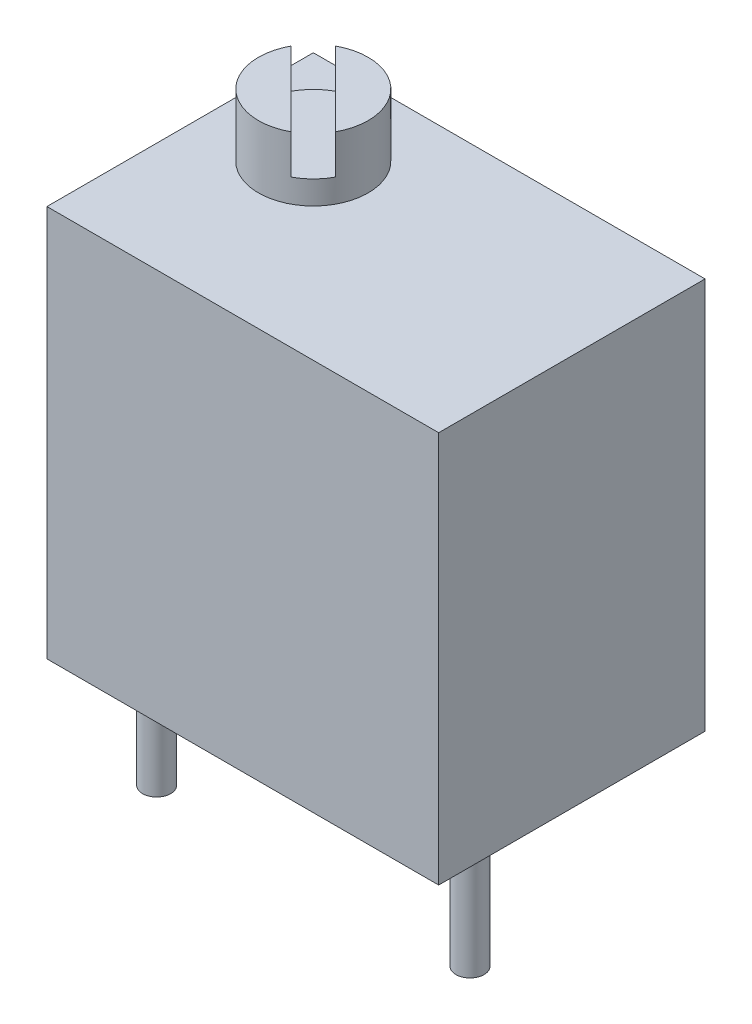
SolidWorks part; units mm, degrees
ref_plane "Front Plane" through (0, 0, 0) normal (0, 0, 1) x (1, 0, 0)
ref_plane "Top Plane" through (0, 0, 0) normal (0, 1, 0) x (1, 0, 0)
ref_plane "Right Plane" through (0, 0, 0) normal (1, 0, 0) x (0, 0, -1)
sketch "Sketch1" plane through (0, 0, 0) normal (0, 1, 0) x (1, 0, 0)
  line L1 (-0.762, -1.016) -> (5.588, -1.016)
  line L2 (-0.762, -1.016) -> (-0.762, 3.302)
  line L3 (-0.762, 3.302) -> (5.588, 3.302)
  line L4 (5.588, -1.016) -> (5.588, 3.302)
  dimension "D1" = 6.35
  dimension "D2" = 4.318
  dimension "D3" = 0.762
  dimension "D4" = 1.016
extrude "Extrude1" add sketch "Sketch1" along normal blind 6.35
sketch "Sketch2" plane through (0, 6.35, 0) normal (0, 1, 0) x (1, 0, 0)
  line L0 (-0.762, 3.302) -> (-0.762, -1.016) construction
  line L1 (5.588, 3.302) -> (-0.762, 3.302) construction
  circle A0 centre (0.762, 1.778) radius 0.889
  dimension "D3" = 1.778
  dimension "D1" = 1.524
  dimension "D2" = 1.524
extrude "Extrude2" add sketch "Sketch2" along normal blind 1.016
sketch "Sketch3" plane through (0, 7.366, 0) normal (0, 1, 0) x (1, 0, 0)
  line L0 (-0.1453, 2.3261) -> (1.3101, 0.8707)
  line L1 (-0.1453, 2.3261) -> (0.2139, 2.6853)
  line L2 (1.3101, 0.8707) -> (1.6693, 1.2299)
  line L3 (0.2139, 2.6853) -> (1.6693, 1.2299)
  line L4 (-0.1453, 2.3261) -> (1.6693, 1.2299) construction
  line L5 (1.3101, 0.8707) -> (0.2139, 2.6853) construction
  line L6 (-0.762, 3.302) -> (-0.762, -1.016) construction
  point P1 (0.762, 1.778)
  dimension "D1" = 0.508
  dimension "D2" = 45
extrude "Extrude3" cut sketch "Sketch3" against normal blind 0.635
sketch "Sketch4" plane through (0, 0, 0) normal (0, -1, 0) x (1, 0, 0)
  circle A0 centre (0, 0) radius 0.2286
  circle A1 centre (5.08, 0) radius 0.2286
  circle A2 centre (2.54, -2.54) radius 0.2286
  dimension "D4" = 0.4572
  dimension "D1" = 2.54
  dimension "D2" = 2.54
  dimension "D3" = 2.54
extrude "Extrude4" add sketch "Sketch4" along normal blind 4.7752
sketch "Sketch5" plane through (0, 0, 1.016) normal (0, 0, 1) x (1, 0, 0)
  line L0 (-0.2286, -4.7752) -> (0.2286, -4.7752) construction
  line L1 (-0.2286, -1.905) -> (5.3086, -1.905)
  line L2 (-0.2286, -1.905) -> (-0.2286, -4.7752)
  line L3 (-0.2286, -4.7752) -> (5.3086, -4.7752)
  line L4 (5.3086, -1.905) -> (5.3086, -4.7752)
  line L5 (-0.2286, 0) -> (-0.2286, -4.7752) construction
  line L6 (5.3086, -4.7752) -> (5.3086, 0) construction
  line L7 (-0.762, 0) -> (5.588, 0) construction
  dimension "D1" = 1.905
extrude "PCB Trim" cut sketch "Sketch5" against normal through all
